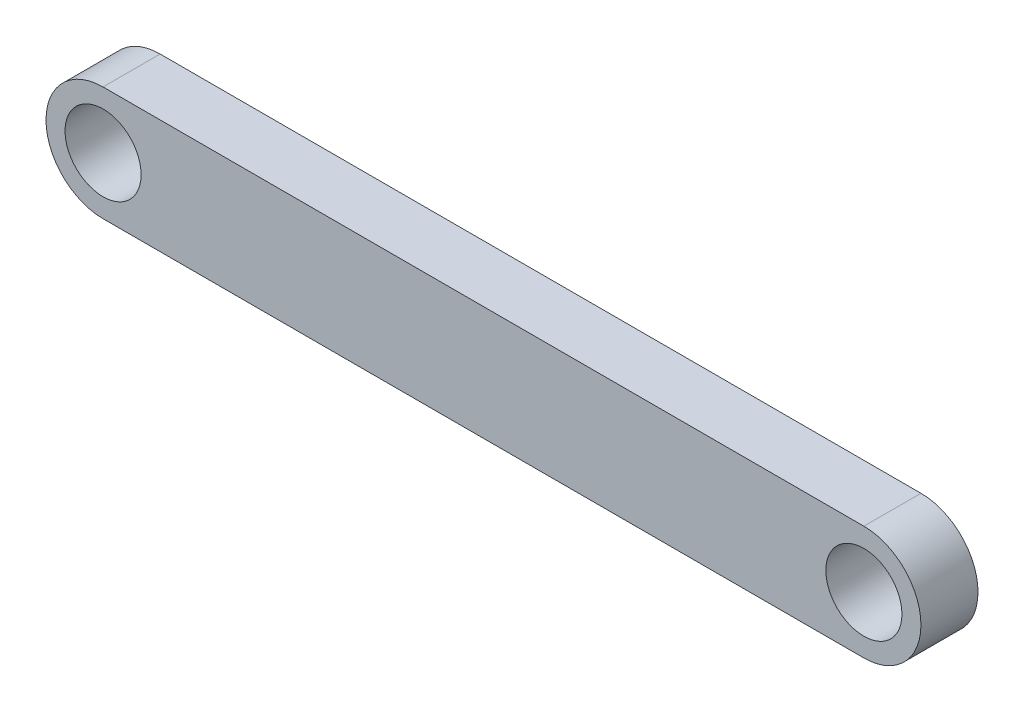
SolidWorks part; units mm, degrees
ref_plane "Front Plane" through (0, 0, 0) normal (0, 0, 1) x (1, 0, 0)
ref_plane "Top Plane" through (0, 0, 0) normal (0, 1, 0) x (1, 0, 0)
ref_plane "Right Plane" through (0, 0, 0) normal (1, 0, 0) x (0, 0, -1)
sketch "Sketch1" plane through (0, 0, 0) normal (0, 0, 1) x (1, 0, 0)
  line L0 (-200, 15.05) -> (0, 15.05)
  line L1 (-200, -14.95) -> (0, -14.95)
  circle A0 centre (-200, 0.05) radius 10
  circle A1 centre (0, 0) radius 10
  arc A2 (-200, -14.95) -> (-200, 15.05) centre (-200, 0.05) cw
  arc A3 (0, -14.95) -> (0, 15.05) centre (0, 0.05) ccw
  dimension "D1" = 200
  dimension "D3" = 20
  dimension "D2" = 30
extrude "Extrude1" add sketch "Sketch1" along normal blind 15
